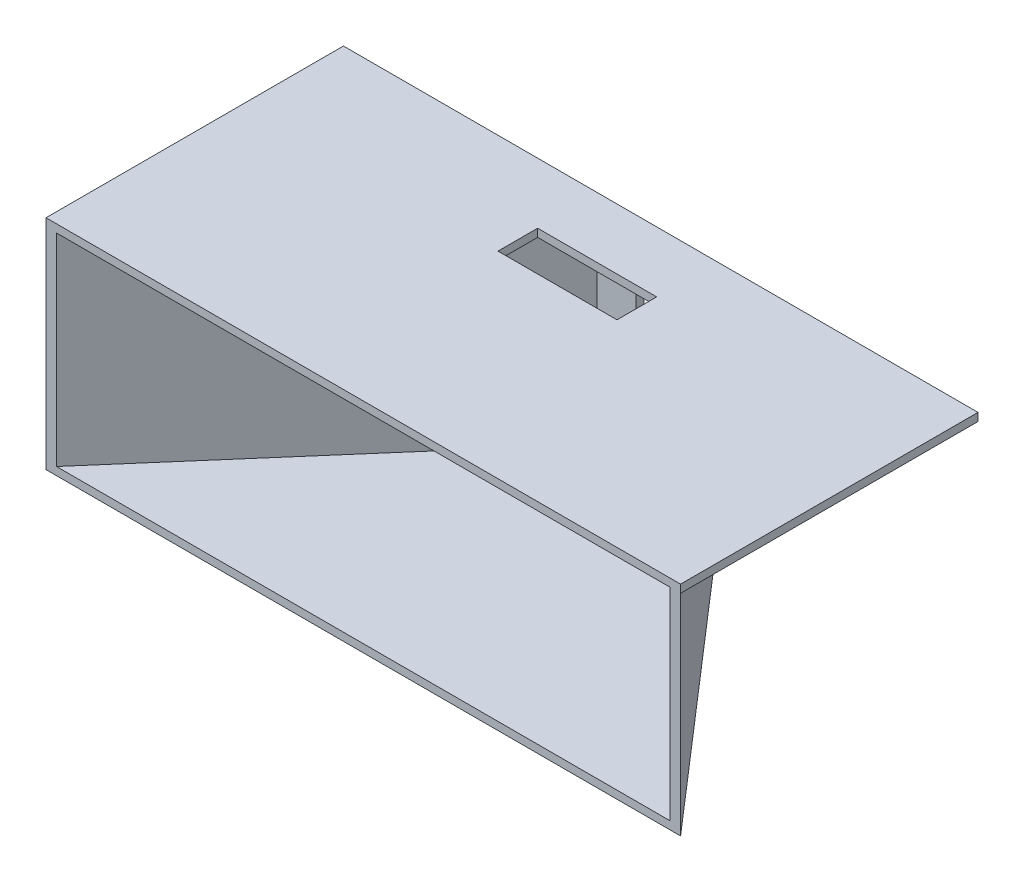
SolidWorks part; units mm, degrees
ref_plane "Front Plane" through (0, 0, 0) normal (0, 0, 1) x (1, 0, 0)
ref_plane "Top Plane" through (0, 0, 0) normal (0, 1, 0) x (1, 0, 0)
ref_plane "Right Plane" through (0, 0, 0) normal (1, 0, 0) x (0, 0, -1)
sketch "Sketch1" plane through (0, 0, 0) normal (0, 1, 0) x (1, 0, 0)
  line L0 (0, 0) -> (-160, 0)
  line L1 (-160, 0) -> (-94.9967, 75)
  line L2 (-94.9967, 75) -> (-64.9967, 75)
  line L3 (-64.9967, 75) -> (0, 0)
  dimension "D1" = 75
  dimension "D2" = 160
  dimension "D3" = 30
  dimension "D5" = 99.245
  dimension "D6" = 99.2493
extrude "Boss-Extrude1" add sketch "Sketch1" against normal blind 55
ref_plane "Plane6" through (-94.9967, 0, -75) normal (0, 1, 0) x (1, 0, 0)
shell "Shell1" thickness 2
sketch "Sketch5" plane through (0, 0, -73) normal (0, 0, 1) x (1, 0, 0)
  line L0 (-65.91, -2) -> (-94.0835, -2) construction
  line L1 (-75.7485, -20.9978) -> (-84.2485, -20.9978)
  line L2 (-75.7485, -20.9978) -> (-75.7485, -12.5)
  line L3 (-75.7485, -12.5) -> (-84.2485, -12.5)
  line L4 (-84.2485, -20.9978) -> (-84.2485, -12.5)
  line L5 (-94.0835, -53) -> (-94.0835, -2) construction
  line L7 (-65.91, -53) -> (-65.91, -2) construction
  dimension "D1" = 9.835
  dimension "D2" = 8.5
  dimension "D3" = 10.5
  dimension "D4" = 9.8385
sketch "Sketch6" plane through (0, 0, 0) normal (0, 1, 0) x (1, 0, 0)
  line L1 (-95.447, 46.2243) -> (-65.447, 46.2243)
  line L2 (-95.447, 46.2243) -> (-95.447, 56.9342)
  line L3 (-95.447, 56.9342) -> (-65.447, 56.9342)
  line L4 (-65.447, 46.2243) -> (-65.447, 56.9342)
  dimension "D1" = 30
extrude "Cut-Extrude3" cut sketch "Sketch6" against normal blind 4
extrude "Cut-Extrude5" cut sketch "Sketch5" against normal blind 6
sketch "Sketch10" plane through (0, 0, 0) normal (0, 0, 1) x (1, 0, 0)
  line L0 (-160, -55) -> (-160, 0) construction
  line L1 (0, 0) -> (-160, 0)
  line L2 (0, 0) -> (0, -2)
  line L3 (0, -2) -> (-160, -2)
  line L4 (-160, 0) -> (-160, -2)
  dimension "D1" = 2
extrude "Boss-Extrude2" add sketch "Sketch10" against normal blind 75
sketch "Sketch11" plane through (0, -2, 0) normal (0, -1, 0) x (-1, 0, 0)
  line L14 (65.7295, 59.7) -> (95.7295, 59.7)
  line L15 (65.7295, 59.7) -> (65.7295, 49.7)
  line L16 (65.7295, 49.7) -> (95.7295, 49.7)
  line L17 (95.7295, 59.7) -> (95.7295, 49.7)
  point P4 (112.0749, 103.7673)
  dimension "D1" = 30
  dimension "D2" = 10
extrude "Cut-Extrude6" cut sketch "Sketch11" against normal blind 8
